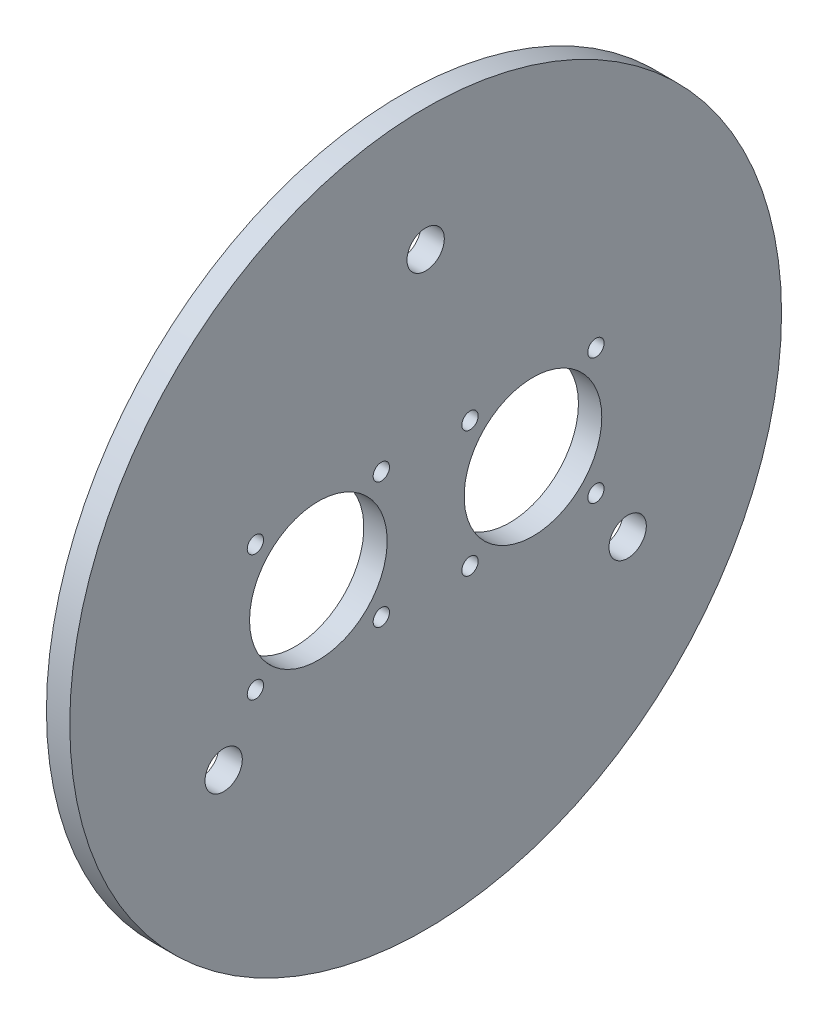
SolidWorks part; units mm, degrees
ref_plane "Front Plane" through (0, 0, 0) normal (0, 0, 1) x (1, 0, 0)
ref_plane "Top Plane" through (0, 0, 0) normal (0, 1, 0) x (1, 0, 0)
ref_plane "Right Plane" through (0, 0, 0) normal (1, 0, 0) x (0, 0, -1)
sketch "Sketch1" plane through (0, 0, 0) normal (1, 0, 0) x (0, 0, -1)
  line L0 (0, -76.29) -> (0, 76.29) construction
  line L1 (-76.29, 0) -> (76.29, 0) construction
  line L2 (23, 0) -> (36.4969, 13.4969) construction
  circle A0 centre (0, 0) radius 76.29
  circle A1 centre (0, 50) radius 4
  circle A2 centre (43.3013, -25) radius 4
  circle A3 centre (-43.3013, -25) radius 4
  circle A4 centre (23, 0) radius 14.75
  circle A5 centre (-23, 0) radius 14.75
  circle A6 centre (36.4969, 13.4969) radius 1.75
  circle A7 centre (36.4969, -13.4969) radius 1.75
  circle A8 centre (9.5031, -13.4969) radius 1.75
  circle A9 centre (9.5031, 13.4969) radius 1.75
  circle A10 centre (-36.4969, -13.4969) radius 1.75
  circle A11 centre (-9.5031, -13.4969) radius 1.75
  circle A12 centre (-9.5031, 13.4969) radius 1.75
  circle A13 centre (-36.4969, 13.4969) radius 1.75
  point P12 (0, 0)
  point P29 (23, 0)
  dimension "D1" = 152.58
  dimension "D2" = 8
  dimension "D5" = 29.5
  dimension "D7" = 3.5
  dimension "D3" = 50
  dimension "D4" = 3
  dimension "D6" = 23
  dimension "D8" = 19.0875
  dimension "D10" = 45
  dimension "D9" = 4
extrude "Boss-Extrude1" add sketch "Sketch1" along normal blind 5
